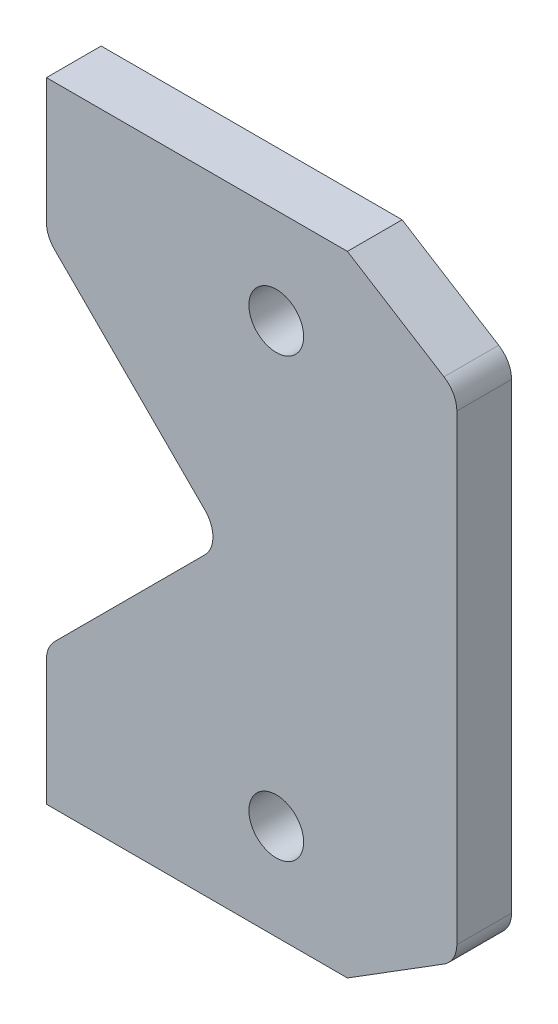
SolidWorks part; units mm, degrees
ref_plane "前视基准面" through (0, 0, 0) normal (0, 0, 1) x (1, 0, 0)
ref_plane "上视基准面" through (0, 0, 0) normal (0, 1, 0) x (1, 0, 0)
ref_plane "右视基准面" through (0, 0, 0) normal (1, 0, 0) x (0, 0, -1)
other "Configuration Table"
sketch "草图1" plane through (0, 0, 0) normal (0, 0, 1) x (1, 0, 0)
  line L0 (0, 0) -> (0, 50000) construction
  line L1 (0, 0) -> (50000, 0) construction
  line L2 (-37.5, 57.5) -> (-37.5, 32.5)
  line L3 (-37.5, 57.5) -> (37.5, 57.5)
  line L4 (-37.5, 57.5) -> (-37.5, -57.5)
  line L5 (-37.5, -57.5) -> (37.5, -57.5)
  line L6 (37.5, 57.5) -> (37.5, -57.5)
  line L7 (-37.5, 32.5) -> (-5, 0)
  line L8 (-37.5, -32.5) -> (-5, 0)
  line L9 (-37.5, -57.5) -> (-37.5, -32.5)
extrude "凸台-拉伸1" add sketch "草图1" along normal blind 10 contours L8 L4 L5 L6 L3 L2 L7
fillet "圆角1" radius 5 3 edges at (-37.5, -32.5, 5) (-5, 0, 5) (-37.5, 32.5, 5)
sketch "草图2" plane through (0, 0, 10) normal (0, 0, 1) x (1, 0, 0)
  line L0 (0, 0) -> (2.5466, 0)
  line L1 (37.5, -57.5) -> (57.5, -57.5)
  line L2 (37.5, -57.5) -> (37.5, 57.5)
  line L3 (37.5, 57.5) -> (57.5, 57.5)
  line L4 (57.5, -57.5) -> (57.5, 57.5)
  line L5 (0, 0) -> (50000, 0) construction
  line L6 (37.5, -57.5) -> (57.5, -45)
  line L7 (57.5, 45) -> (42.9969, 45)
  line L8 (57.5, 45) -> (57.5, -45)
  line L9 (57.5, -45) -> (42.9969, -45)
  line L10 (42.9969, 45) -> (42.9969, -45)
  line L11 (57.5, 45) -> (37.5, 57.5)
  line M14 (37.5, -57.5) -> (37.5, 57.5)
extrude "凸台-拉伸4" add sketch "草图2" against normal blind 10 contours L2 L5 L10 L7 L11 | L10 L5 L8 L7 | L5 L10 L9 L4 | L5 L6 L9 L10 M14
fillet "圆角3" radius 5 2 edges at (57.5, -45, 5) (57.5, 45, 5)
sketch "草图3" plane through (0, 0, 10) normal (0, 0, 1) x (1, 0, 0)
  line L0 (0, 0) -> (0, 50000) construction
  line L1 (0, 0) -> (50000, 0) construction
  line L2 (-37.5, -57.5) -> (37.5, -57.5) construction
  line L3 (-37.5, -34.5711) -> (-37.5, -57.5) construction
  line L4 (17.5, -57.5) -> (17.5, 57.5)
  line L5 (-37.5, 57.5) -> (37.5, 57.5) construction
  line L6 (-37.5, 57.5) -> (-37.5, 34.5711) construction
  line L7 (37.5, 57.5) -> (37.5, -57.5)
  line L8 (17.5, 57.5) -> (37.5, 45)
  line L9 (37.5, 45) -> (17.5, 45)
  line L10 (37.5, 45) -> (37.5, -45)
  line L11 (37.5, -45) -> (17.5, -45)
  line L12 (17.5, 45) -> (17.5, -45)
  line L13 (17.5, -57.5) -> (37.5, -45)
  circle A0 centre (4.5, -32.5) radius 5
  circle A1 centre (4.5, 32.5) radius 5
  line M8 (37.5, -57.5) -> (55.15, -46.4688)
  arc M9 (55.15, -46.4688) -> (57.5, -42.2288) centre (52.5, -42.2288) ccw
  line M10 (57.5, -42.2288) -> (57.5, 42.2288)
  arc M11 (57.5, 42.2288) -> (55.15, 46.4688) centre (52.5, 42.2288) ccw
  line M12 (55.15, 46.4688) -> (37.5, 57.5)
  line M13 (37.5, 57.5) -> (-37.5, 57.5)
  line M21 (-37.5, -57.5) -> (37.5, -57.5)
  dimension "D1" = 25
  dimension "D2" = 42
  dimension "D3" = 55
  dimension "D4" = 90
extrude "切除-拉伸2" cut sketch "草图3" against normal through all contours L8 L7 M13 | L7 M12 M8 M9 M10 M11 | L13 L7 M21 | A0 | A1
fillet "圆角4" radius 5 2 edges at (37.5, -45, 5) (37.5, 45, 5)
sketch "草图4" plane through (0, 0, 10) normal (0, 0, 1) x (1, 0, 0)
  line L0 (4.5, 32.5) -> (4.5, 50032.5) construction
  line L1 (0, 0) -> (50000, 0) construction
  circle A0 centre (4.5, 40) radius 5
  circle A1 centre (4.5, -40) radius 5
  circle M2 centre (4.5, 32.5) radius 5
  circle M17 centre (4.5, -32.5) radius 5
  dimension "D1" = 80
extrude "切除-拉伸5" cut sketch "草图4" against normal through all contours A0 M2 | A1 M17
sketch "草图7" plane through (0, 0, 10) normal (0, 0, 1) x (1, 0, 0)
  circle A0 centre (4.5, -32.5) radius 5
  circle A1 centre (4.5, 32.5) radius 5
  circle A2 centre (4.5, 40) radius 5
  circle A3 centre (4.5, -40) radius 5
  arc M3 (7.8072, 36.25) -> (1.1928, 36.25) centre (4.5, 32.5) cw
  arc M18 (1.1928, -36.25) -> (7.8072, -36.25) centre (4.5, -32.5) cw
extrude "凸台-拉伸7" add sketch "草图7" against normal blind 10 contours A2 M3 | A3 M18
